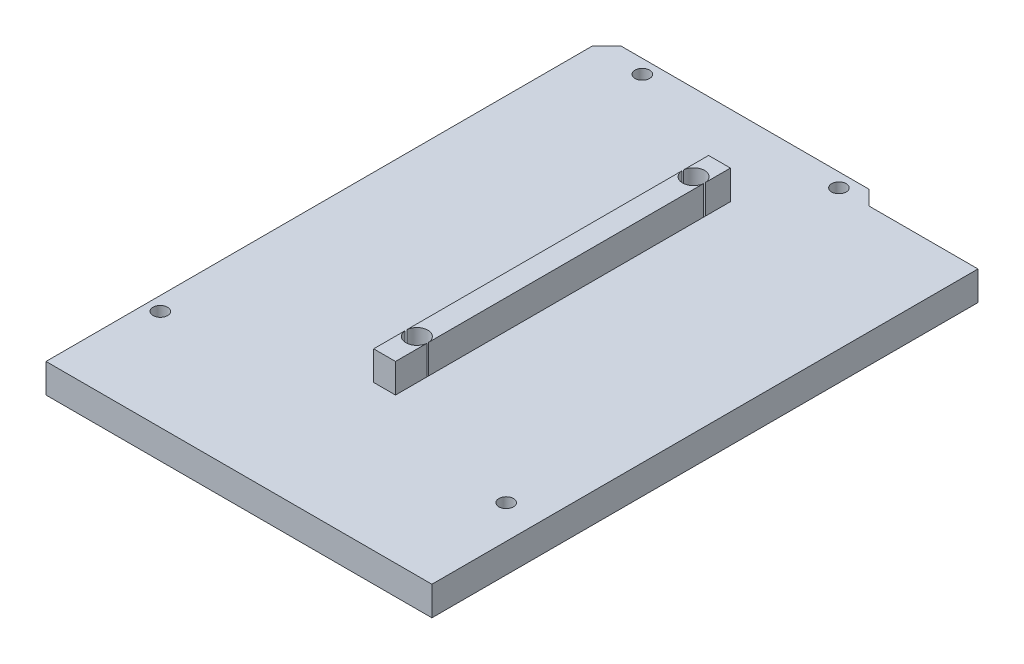
SolidWorks part; units mm, degrees
ref_plane "Спереди" through (0, 0, 0) normal (0, 0, 1) x (1, 0, 0)
ref_plane "Сверху" through (0, 0, 0) normal (0, 1, 0) x (1, 0, 0)
ref_plane "Справа" through (0, 0, 0) normal (1, 0, 0) x (0, 0, -1)
sketch "Эскиз1" plane through (0, 0, 0) normal (0, 1, 0) x (1, 0, 0)
  line L0 (2.3963, 76.8242) -> (36.3963, 76.8242)
  line L5 (36.3963, 76.8242) -> (38.3963, 74.8242)
  line L6 (38.3963, 74.8242) -> (53.3963, 74.8242)
  line L7 (53.3963, 74.8242) -> (53.3963, -0.1758)
  line L8 (53.3963, -0.1758) -> (0.3963, -0.1758)
  line L9 (0.3963, -0.1758) -> (0.3963, 74.8242)
  line L10 (0.3963, 74.8242) -> (2.3963, 76.8242)
  circle A0 centre (7.1963, 74.9242) radius 1
  circle A1 centre (34.1963, 74.9242) radius 1
  circle A2 centre (2.2963, 13.6242) radius 1
  circle A3 centre (48.7963, 14.6242) radius 1
  dimension "D1" = 2
  dimension "D2" = 2
  dimension "D3" = 2
  dimension "D4" = 2
  dimension "D5" = 75
  dimension "D6" = 2.8284
  dimension "D7" = 34
  dimension "D8" = 15
  dimension "D9" = 2.8284
  dimension "D10" = 75
  dimension "D11" = 53
extrude "Бобышка-Вытянуть2" add sketch "Эскиз1" along normal blind 4
sketch "Эскиз3" plane through (0, 4, 0) normal (0, 1, 0) x (1, 0, 0)
  line L0 (0.3963, 74.8242) -> (0.3963, -0.1758) construction
  line L1 (25.3963, 65.8242) -> (28.3963, 65.8242)
  line L2 (25.3963, 65.8242) -> (25.3963, 19.8242)
  line L3 (25.3963, 19.8242) -> (28.3963, 19.8242)
  line L4 (28.3963, 65.8242) -> (28.3963, 19.8242)
  line L5 (53.3963, -0.1758) -> (53.3963, 74.8242) construction
  line L6 (0.3963, -0.1758) -> (53.3963, -0.1758) construction
  dimension "D1" = 46
  dimension "D2" = 3
  dimension "D3" = 25
  dimension "D4" = 25
  dimension "D5" = 20
extrude "Бобышка-Вытянуть3" add sketch "Эскиз3" along normal blind 4
sketch "Эскиз4" plane through (0, 0, 0) normal (0, -1, 0) x (1, 0, 0)
  line L1 (28.3963, -36.5019) -> (28.3963, -65.8242) construction
  line L2 (28.3963, -65.8242) -> (25.3963, -65.8242) construction
  line L4 (25.3963, -19.8242) -> (28.3963, -19.8242) construction
  line L5 (28.3963, -19.8242) -> (28.3963, -36.5019) construction
  line L6 (25.3963, -19.8242) -> (28.3963, -19.8242) construction
  line L7 (28.3963, -65.8242) -> (25.3963, -65.8242) construction
  line L9 (28.3963, -19.8242) -> (28.3963, -65.8242) construction
  line L10 (26.8963, -24.263) -> (26.8963, -62.263) construction
  line L11 (25.3963, -19.8242) -> (25.3963, -65.8242) construction
  circle A0 centre (26.8963, -24.263) radius 1.505
  circle A1 centre (26.8963, -62.263) radius 1.505
  point P11 (26.8963, -65.8242)
  point P14 (28.3963, -36.5019)
  dimension "D1" = 3.01
  dimension "D2" = 3.01
  dimension "D3" = 38
  dimension "D8" = 1.5
  dimension "D6" = 3
  dimension "D4" = 0
  dimension "D5" = 0
  dimension "D7" = 0
extrude "Вырез-Вытянуть7" cut sketch "Эскиз4" against normal blind 8
chamfer "Фаска1" distance 1.5 angle 45 1 edges at (26.8963, 0, -63.768)
chamfer "Фаска2" distance 1.5 angle 45 1 edges at (26.8963, 0, -25.768)
